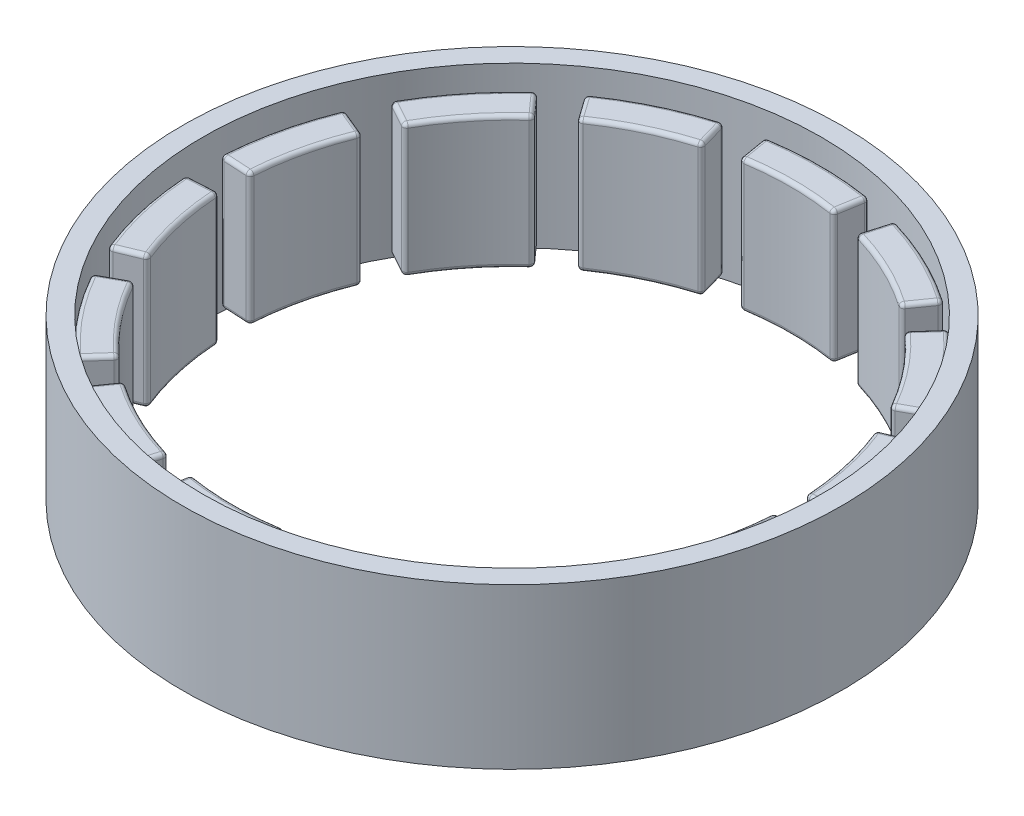
SolidWorks part; units mm, degrees
material "6061-T6 (SS)"
ref_plane "Front Plane" through (0, 0, 0) normal (0, 0, 1) x (1, 0, 0)
ref_plane "Top Plane" through (0, 0, 0) normal (0, 1, 0) x (1, 0, 0)
ref_plane "Right Plane" through (0, 0, 0) normal (1, 0, 0) x (0, 0, -1)
sketch "Sketch1" plane through (0, 0, 0) normal (0, 0, 1) x (1, 0, 0)
  line L0 (0, 0) -> (0, 18.2227) construction
  line L2 (-19.825, 0) -> (-21.125, 0)
  line L3 (-19.825, 0) -> (-19.825, 10.25)
  line L4 (-19.825, 10.25) -> (-21.125, 10.25)
  line L5 (-21.125, 0) -> (-21.125, 10.25)
  dimension "D1" = 42.25
  dimension "D2" = 1.3
  dimension "D3" = 10.25
revolve "Revolve1" add sketch "Sketch1" angle 360 about L0
sketch "Sketch3" plane through (0, 0, 0) normal (0, -1, 0) x (1, 0, 0)
  line L0 (-3.293, 19.2944) -> (-3.0406, 17.8157)
  line L1 (3.0406, 17.8157) -> (3.293, 19.2944)
  line L2 (5.4047, 18.8124) -> (4.9904, 17.3706)
  line L3 (10.4694, 14.7321) -> (11.3384, 15.9549)
  line L4 (13.0318, 14.6044) -> (12.0331, 13.4851)
  line L5 (15.8246, 8.7307) -> (17.1381, 9.4553)
  line L6 (18.0779, 7.5038) -> (16.6924, 6.9287)
  line L7 (18.0456, 1) -> (19.5434, 1.083)
  line L8 (19.5434, -1.083) -> (18.0456, -1)
  line L9 (16.6924, -6.9287) -> (18.0779, -7.5038)
  line L10 (17.1381, -9.4553) -> (15.8246, -8.7307)
  line L11 (12.0331, -13.4851) -> (13.0318, -14.6044)
  line L12 (11.3384, -15.9549) -> (10.4694, -14.7321)
  line L13 (4.9904, -17.3706) -> (5.4047, -18.8124)
  line L14 (3.293, -19.2944) -> (3.0406, -17.8157)
  line L15 (-3.0406, -17.8157) -> (-3.293, -19.2944)
  line L16 (-5.4047, -18.8124) -> (-4.9904, -17.3706)
  line L17 (-10.4694, -14.7321) -> (-11.3384, -15.9549)
  line L18 (-13.0318, -14.6044) -> (-12.0331, -13.4851)
  line L19 (-15.8246, -8.7307) -> (-17.1381, -9.4553)
  line L20 (-18.0779, -7.5038) -> (-16.6924, -6.9287)
  line L21 (-18.0456, -1) -> (-19.5434, -1.083)
  line L22 (-19.5434, 1.083) -> (-18.0456, 1)
  line L23 (-16.6924, 6.9287) -> (-18.0779, 7.5038)
  line L24 (-17.1381, 9.4553) -> (-15.8246, 8.7307)
  line L25 (-12.0331, 13.4851) -> (-13.0318, 14.6044)
  line L26 (-11.3384, 15.9549) -> (-10.4694, 14.7321)
  line L27 (-4.9904, 17.3706) -> (-5.4047, 18.8124)
  arc A0 (-3.0854, 19.5834) -> (3.0854, 19.5834) centre (0, 0) cw
  circle A1 centre (0, 0) radius 19.825 construction
  arc A2 (-2.7555, 17.6107) -> (2.7555, 17.6107) centre (0, 0) cw
  arc A3 (-3.7106, 17.4345) -> (3.4908, 17.4799) centre (0, 0) cw construction
  arc A4 (2.7555, 17.6107) -> (3.0406, 17.8157) centre (2.7942, 17.8577) ccw
  arc A5 (-4.127, 19.3907) -> (3.8824, 19.4411) centre (0, 0) cw construction
  arc A6 (3.0854, 19.5834) -> (3.293, 19.2944) centre (3.0465, 19.3365) cw
  arc A7 (-3.0854, 19.5834) -> (-3.293, 19.2944) centre (-3.0465, 19.3365) ccw
  arc A8 (-2.7555, 17.6107) -> (-3.0406, 17.8157) centre (-2.7942, 17.8577) cw
  arc A9 (5.717, 18.9828) -> (11.2768, 16.3053) centre (0, 0) cw
  arc A10 (5.1584, 17.0623) -> (10.1236, 14.6711) centre (0, 0) cw
  arc A11 (10.1236, 14.6711) -> (10.4694, 14.7321) centre (10.2656, 14.8769) ccw
  arc A12 (11.2768, 16.3053) -> (11.3384, 15.9549) centre (11.1346, 16.0997) cw
  arc A13 (5.717, 18.9828) -> (5.4047, 18.8124) centre (5.645, 18.7434) ccw
  arc A14 (5.1584, 17.0623) -> (4.9904, 17.3706) centre (5.2307, 17.3016) cw
  arc A15 (13.3872, 14.6224) -> (17.2347, 9.7978) centre (0, 0) cw
  arc A16 (12.0506, 13.1345) -> (15.4867, 8.8258) centre (0, 0) cw
  arc A17 (15.4867, 8.8258) -> (15.8246, 8.7307) centre (15.7039, 8.9496) ccw
  arc A18 (17.2347, 9.7978) -> (17.1381, 9.4553) centre (17.0173, 9.6742) cw
  arc A19 (13.3872, 14.6224) -> (13.0318, 14.6044) centre (13.2184, 14.438) ccw
  arc A20 (12.0506, 13.1345) -> (12.0331, 13.4851) centre (12.2196, 13.3187) cw
  arc A21 (18.4059, 7.3658) -> (19.779, 1.3496) centre (0, 0) cw
  arc A22 (16.556, 6.6052) -> (17.7824, 1.2323) centre (0, 0) cw
  arc A23 (17.7824, 1.2323) -> (18.0456, 1) centre (18.0318, 1.2496) ccw
  arc A24 (19.779, 1.3496) -> (19.5434, 1.083) centre (19.5296, 1.3326) cw
  arc A25 (18.4059, 7.3658) -> (18.0779, 7.5038) centre (18.1738, 7.2729) ccw
  arc A26 (16.556, 6.6052) -> (16.6924, 6.9287) centre (16.7882, 6.6978) cw
  arc A27 (19.779, -1.3496) -> (18.4059, -7.3658) centre (0, 0) cw
  arc A28 (17.7824, -1.2323) -> (16.556, -6.6052) centre (0, 0) cw
  arc A29 (16.556, -6.6052) -> (16.6924, -6.9287) centre (16.7882, -6.6978) ccw
  arc A30 (18.4059, -7.3658) -> (18.0779, -7.5038) centre (18.1738, -7.2729) cw
  arc A31 (19.779, -1.3496) -> (19.5434, -1.083) centre (19.5296, -1.3326) ccw
  arc A32 (17.7824, -1.2323) -> (18.0456, -1) centre (18.0318, -1.2496) cw
  arc A33 (17.2347, -9.7978) -> (13.3872, -14.6224) centre (0, 0) cw
  arc A34 (15.4867, -8.8258) -> (12.0506, -13.1345) centre (0, 0) cw
  arc A35 (12.0506, -13.1345) -> (12.0331, -13.4851) centre (12.2196, -13.3187) ccw
  arc A36 (13.3872, -14.6224) -> (13.0318, -14.6044) centre (13.2184, -14.438) cw
  arc A37 (17.2347, -9.7978) -> (17.1381, -9.4553) centre (17.0173, -9.6742) ccw
  arc A38 (15.4867, -8.8258) -> (15.8246, -8.7307) centre (15.7039, -8.9496) cw
  arc A39 (11.2768, -16.3053) -> (5.717, -18.9828) centre (0, 0) cw
  arc A40 (10.1236, -14.6711) -> (5.1584, -17.0623) centre (0, 0) cw
  arc A41 (5.1584, -17.0623) -> (4.9904, -17.3706) centre (5.2307, -17.3016) ccw
  arc A42 (5.717, -18.9828) -> (5.4047, -18.8124) centre (5.645, -18.7434) cw
  arc A43 (11.2768, -16.3053) -> (11.3384, -15.9549) centre (11.1346, -16.0997) ccw
  arc A44 (10.1236, -14.6711) -> (10.4694, -14.7321) centre (10.2656, -14.8769) cw
  arc A45 (3.0854, -19.5834) -> (-3.0854, -19.5834) centre (0, 0) cw
  arc A46 (2.7555, -17.6107) -> (-2.7555, -17.6107) centre (0, 0) cw
  arc A47 (-2.7555, -17.6107) -> (-3.0406, -17.8157) centre (-2.7942, -17.8577) ccw
  arc A48 (-3.0854, -19.5834) -> (-3.293, -19.2944) centre (-3.0465, -19.3365) cw
  arc A49 (3.0854, -19.5834) -> (3.293, -19.2944) centre (3.0465, -19.3365) ccw
  arc A50 (2.7555, -17.6107) -> (3.0406, -17.8157) centre (2.7942, -17.8577) cw
  arc A51 (-5.717, -18.9828) -> (-11.2768, -16.3053) centre (0, 0) cw
  arc A52 (-5.1584, -17.0623) -> (-10.1236, -14.6711) centre (0, 0) cw
  arc A53 (-10.1236, -14.6711) -> (-10.4694, -14.7321) centre (-10.2656, -14.8769) ccw
  arc A54 (-11.2768, -16.3053) -> (-11.3384, -15.9549) centre (-11.1346, -16.0997) cw
  arc A55 (-5.717, -18.9828) -> (-5.4047, -18.8124) centre (-5.645, -18.7434) ccw
  arc A56 (-5.1584, -17.0623) -> (-4.9904, -17.3706) centre (-5.2307, -17.3016) cw
  arc A57 (-13.3872, -14.6224) -> (-17.2347, -9.7978) centre (0, 0) cw
  arc A58 (-12.0506, -13.1345) -> (-15.4867, -8.8258) centre (0, 0) cw
  arc A59 (-15.4867, -8.8258) -> (-15.8246, -8.7307) centre (-15.7039, -8.9496) ccw
  arc A60 (-17.2347, -9.7978) -> (-17.1381, -9.4553) centre (-17.0173, -9.6742) cw
  arc A61 (-13.3872, -14.6224) -> (-13.0318, -14.6044) centre (-13.2184, -14.438) ccw
  arc A62 (-12.0506, -13.1345) -> (-12.0331, -13.4851) centre (-12.2196, -13.3187) cw
  arc A63 (-18.4059, -7.3658) -> (-19.779, -1.3496) centre (0, 0) cw
  arc A64 (-16.556, -6.6052) -> (-17.7824, -1.2323) centre (0, 0) cw
  arc A65 (-17.7824, -1.2323) -> (-18.0456, -1) centre (-18.0318, -1.2496) ccw
  arc A66 (-19.779, -1.3496) -> (-19.5434, -1.083) centre (-19.5296, -1.3326) cw
  arc A67 (-18.4059, -7.3658) -> (-18.0779, -7.5038) centre (-18.1738, -7.2729) ccw
  arc A68 (-16.556, -6.6052) -> (-16.6924, -6.9287) centre (-16.7882, -6.6978) cw
  arc A69 (-19.779, 1.3496) -> (-18.4059, 7.3658) centre (0, 0) cw
  arc A70 (-17.7824, 1.2323) -> (-16.556, 6.6052) centre (0, 0) cw
  arc A71 (-16.556, 6.6052) -> (-16.6924, 6.9287) centre (-16.7882, 6.6978) ccw
  arc A72 (-18.4059, 7.3658) -> (-18.0779, 7.5038) centre (-18.1738, 7.2729) cw
  arc A73 (-19.779, 1.3496) -> (-19.5434, 1.083) centre (-19.5296, 1.3326) ccw
  arc A74 (-17.7824, 1.2323) -> (-18.0456, 1) centre (-18.0318, 1.2496) cw
  arc A75 (-17.2347, 9.7978) -> (-13.3872, 14.6224) centre (0, 0) cw
  arc A76 (-15.4867, 8.8258) -> (-12.0506, 13.1345) centre (0, 0) cw
  arc A77 (-12.0506, 13.1345) -> (-12.0331, 13.4851) centre (-12.2196, 13.3187) ccw
  arc A78 (-13.3872, 14.6224) -> (-13.0318, 14.6044) centre (-13.2184, 14.438) cw
  arc A79 (-17.2347, 9.7978) -> (-17.1381, 9.4553) centre (-17.0173, 9.6742) ccw
  arc A80 (-15.4867, 8.8258) -> (-15.8246, 8.7307) centre (-15.7039, 8.9496) cw
  arc A81 (-11.2768, 16.3053) -> (-5.717, 18.9828) centre (0, 0) cw
  arc A82 (-10.1236, 14.6711) -> (-5.1584, 17.0623) centre (0, 0) cw
  arc A83 (-5.1584, 17.0623) -> (-4.9904, 17.3706) centre (-5.2307, 17.3016) ccw
  arc A84 (-5.717, 18.9828) -> (-5.4047, 18.8124) centre (-5.645, 18.7434) cw
  arc A85 (-11.2768, 16.3053) -> (-11.3384, 15.9549) centre (-11.1346, 16.0997) ccw
  arc A86 (-10.1236, 14.6711) -> (-10.4694, 14.7321) centre (-10.2656, 14.8769) cw
  point P6 (0, 19.825)
  point P15 (3.3353, 19.5424)
  point P181 (0, 0)
  dimension "D2" = 0.25
  dimension "D4" = 2
  dimension "D1" = 2
  dimension "D3" = 14
extrude "Boss-Extrude1" add sketch "Sketch3" against normal offset from surface (8.5 mm away) 1.5 from offset 0.25 separate body up to face at (0, 10.25, -21.125) offset against normal yes
fillet "Fillet1" radius 0.25 16 edges at (7.734, 0.25, 16.0598) (5.0112, 0.25, 17.182) (5.1976, 0.25, 18.0915) (5.5253, 0.25, 18.9629) (8.6017, 0.25, 17.8617) (11.3808, 0.25, 16.143) (10.9039, 0.25, 15.3435) (10.309, 0.25, 14.6307) (10.9039, 8.75, 15.3435) (11.3808, 8.75, 16.143) (8.6017, 8.75, 17.8617) (5.5253, 8.75, 18.9629) (5.1976, 8.75, 18.0915) (5.0112, 8.75, 17.182) (7.734, 8.75, 16.0598) (10.309, 8.75, 14.6307)
fillet "Fillet2" radius 0.25 16 edges at (3.1668, 8.75, 18.555) (3.2496, 8.75, 19.4823) (0, 8.75, 19.825) (-3.2496, 8.75, 19.4823) (-3.1668, 8.75, 18.555) (-2.9401, 8.75, 17.6547) (0, 8.75, 17.825) (2.9401, 8.75, 17.6547) (0, 0.25, 17.825) (-2.9401, 0.25, 17.6547) (-3.1668, 0.25, 18.555) (-3.2496, 0.25, 19.4823) (0, 0.25, 19.825) (3.2496, 0.25, 19.4823) (3.1668, 0.25, 18.555) (2.9401, 0.25, 17.6547)
fillet "Fillet3" radius 0.25 16 edges at (-7.734, 0.25, 16.0598) (-10.309, 0.25, 14.6307) (-10.9039, 0.25, 15.3435) (-11.3808, 0.25, 16.143) (-8.6017, 0.25, 17.8617) (-5.5253, 0.25, 18.9629) (-5.1976, 0.25, 18.0915) (-5.0112, 0.25, 17.182) (-5.1976, 8.75, 18.0915) (-5.5253, 8.75, 18.9629) (-8.6017, 8.75, 17.8617) (-11.3808, 8.75, 16.143) (-10.9039, 8.75, 15.3435) (-10.309, 8.75, 14.6307) (-7.734, 8.75, 16.0598) (-5.0112, 8.75, 17.182)
fillet "Fillet4" radius 0.25 16 edges at (-12.5325, 8.75, 14.0448) (-13.2058, 8.75, 14.6877) (-15.4998, 8.75, 12.3607) (-17.258, 8.75, 9.6064) (-16.4814, 8.75, 9.093) (-15.6361, 8.75, 8.7089) (-13.9361, 8.75, 11.1137) (-11.9699, 8.75, 13.3062) (-13.9361, 0.25, 11.1137) (-15.6361, 0.25, 8.7089) (-16.4814, 0.25, 9.093) (-17.258, 0.25, 9.6064) (-15.4998, 0.25, 12.3607) (-13.2058, 0.25, 14.6877) (-12.5325, 0.25, 14.0448) (-11.9699, 0.25, 13.3062)
fillet "Fillet5" radius 0.25 16 edges at (-17.3781, 0.25, 3.9664) (-17.8663, 0.25, 1.0622) (-18.7945, 0.25, 1.0415) (-19.7169, 0.25, 1.1671) (-19.3279, 0.25, 4.4115) (-18.2707, 0.25, 7.5033) (-17.3852, 0.25, 7.2163) (-16.5579, 0.25, 6.7949) (-17.3852, 8.75, 7.2163) (-18.2707, 8.75, 7.5033) (-19.3279, 8.75, 4.4115) (-19.7169, 8.75, 1.1671) (-18.7945, 8.75, 1.0415) (-17.8663, 8.75, 1.0622) (-17.3781, 8.75, 3.9664) (-16.5579, 8.75, 6.7949)
fillet "Fillet6" radius 0.25 16 edges at (-18.7945, 8.75, -1.0415) (-19.7169, 8.75, -1.1671) (-19.3279, 8.75, -4.4115) (-18.2707, 8.75, -7.5033) (-17.3852, 8.75, -7.2163) (-16.5579, 8.75, -6.7949) (-17.3781, 8.75, -3.9664) (-17.8663, 8.75, -1.0622) (-17.3781, 0.25, -3.9664) (-16.5579, 0.25, -6.7949) (-17.3852, 0.25, -7.2163) (-18.2707, 0.25, -7.5033) (-19.3279, 0.25, -4.4115) (-19.7169, 0.25, -1.1671) (-18.7945, 0.25, -1.0415) (-17.8663, 0.25, -1.0622)
fillet "Fillet7" radius 0.25 16 edges at (-13.9361, 0.25, -11.1137) (-11.9699, 0.25, -13.3062) (-12.5325, 0.25, -14.0448) (-13.2058, 0.25, -14.6877) (-15.4998, 0.25, -12.3607) (-17.258, 0.25, -9.6064) (-16.4814, 0.25, -9.093) (-15.6361, 0.25, -8.7089) (-16.4814, 8.75, -9.093) (-17.258, 8.75, -9.6064) (-15.4998, 8.75, -12.3607) (-13.2058, 8.75, -14.6877) (-12.5325, 8.75, -14.0448) (-11.9699, 8.75, -13.3062) (-13.9361, 8.75, -11.1137) (-15.6361, 8.75, -8.7089)
fillet "Fillet8" radius 0.25 16 edges at (-10.9039, 8.75, -15.3435) (-11.3808, 8.75, -16.143) (-8.6017, 8.75, -17.8617) (-5.5253, 8.75, -18.9629) (-5.1976, 8.75, -18.0915) (-5.0112, 8.75, -17.182) (-7.734, 8.75, -16.0598) (-10.309, 8.75, -14.6307) (-7.734, 0.25, -16.0598) (-5.0112, 0.25, -17.182) (-5.1976, 0.25, -18.0915) (-5.5253, 0.25, -18.9629) (-8.6017, 0.25, -17.8617) (-11.3808, 0.25, -16.143) (-10.9039, 0.25, -15.3435) (-10.309, 0.25, -14.6307)
fillet "Fillet9" radius 0.25 16 edges at (0, 0.25, -17.825) (2.9401, 0.25, -17.6547) (3.1668, 0.25, -18.555) (3.2496, 0.25, -19.4823) (0, 0.25, -19.825) (-3.2496, 0.25, -19.4823) (-3.1668, 0.25, -18.555) (-2.9401, 0.25, -17.6547) (-3.1668, 8.75, -18.555) (-3.2496, 8.75, -19.4823) (0, 8.75, -19.825) (3.2496, 8.75, -19.4823) (3.1668, 8.75, -18.555) (2.9401, 8.75, -17.6547) (0, 8.75, -17.825) (-2.9401, 8.75, -17.6547)
fillet "Fillet10" radius 0.25 16 edges at (5.1976, 8.75, -18.0915) (5.5253, 8.75, -18.9629) (8.6017, 8.75, -17.8617) (11.3808, 8.75, -16.143) (10.9039, 8.75, -15.3435) (10.309, 8.75, -14.6307) (7.734, 8.75, -16.0598) (5.0112, 8.75, -17.182) (7.734, 0.25, -16.0598) (10.309, 0.25, -14.6307) (10.9039, 0.25, -15.3435) (11.3808, 0.25, -16.143) (8.6017, 0.25, -17.8617) (5.5253, 0.25, -18.9629) (5.1976, 0.25, -18.0915) (5.0112, 0.25, -17.182)
fillet "Fillet11" radius 0.25 16 edges at (13.9361, 0.25, -11.1137) (15.6361, 0.25, -8.7089) (16.4814, 0.25, -9.093) (17.258, 0.25, -9.6064) (15.4998, 0.25, -12.3607) (13.2058, 0.25, -14.6877) (12.5325, 0.25, -14.0448) (11.9699, 0.25, -13.3062) (12.5325, 8.75, -14.0448) (13.2058, 8.75, -14.6877) (15.4998, 8.75, -12.3607) (17.258, 8.75, -9.6064) (16.4814, 8.75, -9.093) (15.6361, 8.75, -8.7089) (13.9361, 8.75, -11.1137) (11.9699, 8.75, -13.3062)
fillet "Fillet12" radius 0.25 16 edges at (17.3852, 8.75, -7.2163) (18.2707, 8.75, -7.5033) (19.3279, 8.75, -4.4115) (19.7169, 8.75, -1.1671) (18.7945, 8.75, -1.0415) (17.8663, 8.75, -1.0622) (17.3781, 8.75, -3.9664) (16.5579, 8.75, -6.7949) (17.3781, 0.25, -3.9664) (17.8663, 0.25, -1.0622) (18.7945, 0.25, -1.0415) (19.7169, 0.25, -1.1671) (19.3279, 0.25, -4.4115) (18.2707, 0.25, -7.5033) (17.3852, 0.25, -7.2163) (16.5579, 0.25, -6.7949)
fillet "Fillet13" radius 0.25 16 edges at (17.3781, 0.25, 3.9664) (16.5579, 0.25, 6.7949) (17.3852, 0.25, 7.2163) (18.2707, 0.25, 7.5033) (19.3279, 0.25, 4.4115) (19.7169, 0.25, 1.1671) (18.7945, 0.25, 1.0415) (17.8663, 0.25, 1.0622) (18.7945, 8.75, 1.0415) (19.7169, 8.75, 1.1671) (19.3279, 8.75, 4.4115) (18.2707, 8.75, 7.5033) (17.3852, 8.75, 7.2163) (16.5579, 8.75, 6.7949) (17.3781, 8.75, 3.9664) (17.8663, 8.75, 1.0622)
fillet "Fillet14" radius 0.25 16 edges at (16.4814, 8.75, 9.093) (17.258, 8.75, 9.6064) (15.4998, 8.75, 12.3607) (13.2058, 8.75, 14.6877) (12.5325, 8.75, 14.0448) (11.9699, 8.75, 13.3062) (13.9361, 8.75, 11.1137) (15.6361, 8.75, 8.7089) (13.9361, 0.25, 11.1137) (11.9699, 0.25, 13.3062) (12.5325, 0.25, 14.0448) (13.2058, 0.25, 14.6877) (15.4998, 0.25, 12.3607) (17.258, 0.25, 9.6064) (16.4814, 0.25, 9.093) (15.6361, 0.25, 8.7089)
